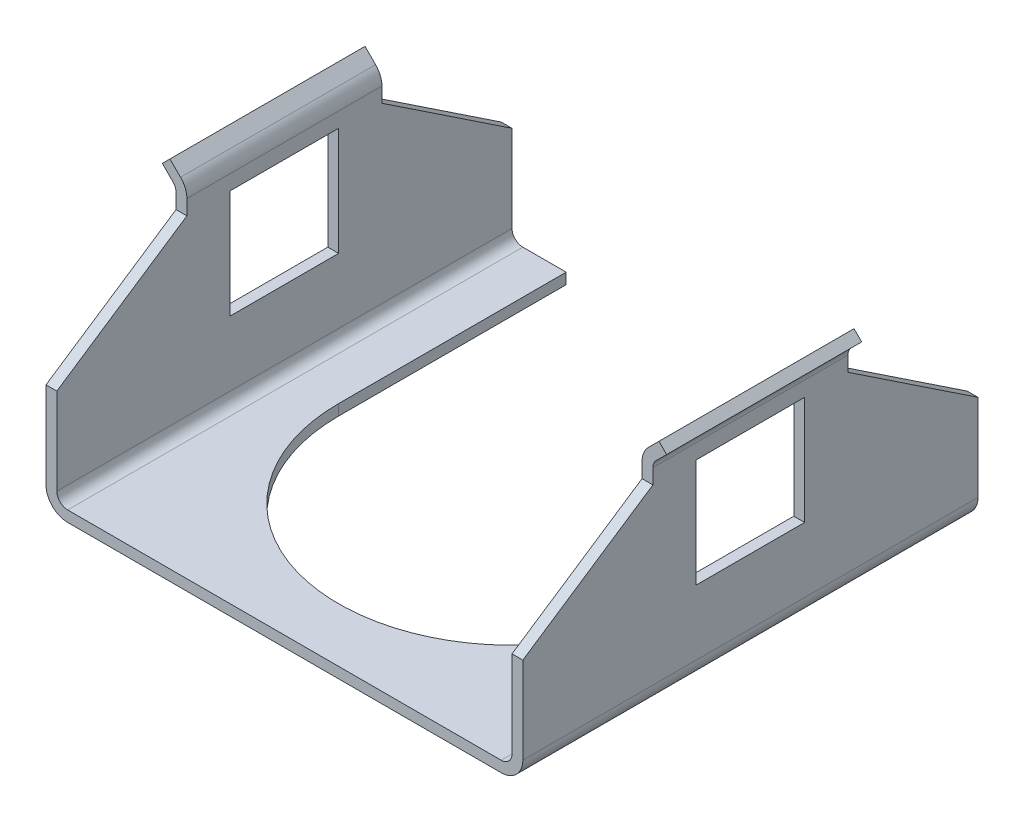
SolidWorks part; units mm, degrees
ref_plane "Front Plane" through (0, 0, 0) normal (0, 0, 1) x (1, 0, 0)
ref_plane "Top Plane" through (0, 0, 0) normal (0, 1, 0) x (1, 0, 0)
ref_plane "Right Plane" through (0, 0, 0) normal (1, 0, 0) x (0, 0, -1)
sketch "Sketch2" plane through (0, 0, 0) normal (0, 1, 0) x (1, 0, 0)
  line L1 (-10.5, 10.5) -> (10.5, 10.5)
  line L2 (-10.5, 10.5) -> (-10.5, -10.5)
  line L3 (-10.5, -10.5) -> (10.5, -10.5)
  line L4 (10.5, 10.5) -> (10.5, -10.5)
  line L5 (-10.5, 10.5) -> (10.5, -10.5) construction
  line L6 (-10.5, -10.5) -> (10.5, 10.5) construction
  circle A0 centre (0, 0) radius 8
  dimension "D1" = 16
  dimension "D2" = 21
extrude "Boss-Extrude1" add sketch "Sketch2" along normal blind 0.5
sketch "Sketch3" plane through (0, 0.5, 0) normal (0, 1, 0) x (1, 0, 0)
  line L0 (-8, 0) -> (-8, 10.5)
  line L1 (10.5, 10.5) -> (-10.5, 10.5) construction
  line L2 (-8, 10.5) -> (-8, 11.596)
  line L3 (8, 0) -> (8, 11.596)
  line L4 (-8, 11.596) -> (8, 11.596)
  circle A0 centre (0, 0) radius 8 construction
  arc A1 (-8, 0) -> (8, 0) centre (0, 0) ccw
extrude "Cut-Extrude1" cut sketch "Sketch3" against normal blind 1.5
sketch "Sketch4" plane through (10.5, 0, 0) normal (1, 0, 0) x (0, 0, -1)
  line L0 (-10.5, 0.5) -> (-10.5, 0) construction
  line L1 (-10.5, 0) -> (10.5, 0)
  line L2 (-10.5, 0) -> (-10.5, 9)
  line L3 (-10.5, 9) -> (10.5, 9)
  line L4 (10.5, 0) -> (10.5, 9)
  dimension "D1" = 9
  dimension "D2" = 21
extrude "Boss-Extrude2" add sketch "Sketch4" along normal blind 0.5
sketch "Sketch5" plane through (11, 0, 0) normal (1, 0, 0) x (0, 0, -1)
  line L0 (0, 0) -> (0, 9) construction
  line L1 (0, 9) -> (2.5, 9) construction
  line L3 (2.5, 9) -> (-2.5, 9)
  line L4 (2.5, 9) -> (2.5, 4)
  line L5 (2.5, 4) -> (-2.5, 4)
  line L6 (-2.5, 9) -> (-2.5, 4)
  dimension "D1" = 9
  dimension "D2" = 2.5
  dimension "D3" = 5
extrude "Cut-Extrude2" cut sketch "Sketch5" against normal through all both and the other way through all
sketch "Sketch6" plane through (11, 0, 0) normal (1, 0, 0) x (0, 0, -1)
  line L0 (10.5, 5) -> (4.5, 9)
  line L1 (10.5, 0) -> (10.5, 9) construction
  line L2 (10.5, 9) -> (2.5, 9) construction
  line L3 (4.5, 9) -> (4.5, 12.4835)
  line L4 (4.5, 12.4835) -> (11.7348, 12.4835)
  line L5 (11.7348, 12.4835) -> (11.7348, 5)
  line L6 (11.7348, 5) -> (10.5, 5)
  line L7 (-10.5, 0) -> (10.5, 0) construction
  dimension "D1" = 5
  dimension "D2" = 6
extrude "Cut-Extrude3" cut sketch "Sketch6" against normal blind 1.5
mirror "Mirror1" about plane through (0, 0, 0) normal (0, 0, 1) of "Cut-Extrude3"
fillet "Fillet1" radius 1 1 edges at (11, 0, 0)
fillet "Fillet2" radius 0.5 1 edges at (10.5, 0.5, 0)
sketch "Sketch7" plane through (0, 0, 0) normal (0, 0, 1) x (1, 0, 0)
  line L0 (10.75, 9) -> (10.75, 10)
  line L1 (10.5, 9) -> (11, 9) construction
  line L2 (10.75, 10) -> (11.4571, 10.7071)
  dimension "D1" = 1
  dimension "D2" = 1
  dimension "D3" = 135
extrude "Extrude-Thin1" add sketch "Sketch7" along normal mid plane 9 thin thin type mid plane wall 0.5
fillet "Fillet3" radius 0.5 1 edges at (11, 9.8964, 0)
fillet "Fillet4" radius 1 1 edges at (10.5, 10.1036, 0)
mirror "Mirror2" about plane through (0, 0, 0) normal (1, 0, 0) of "Extrude-Thin1", "Boss-Extrude2"
sketch "Sketch8" plane through (-10.5, 0, 0) normal (1, 0, 0) x (0, 0, -1)
  line L0 (4.5, 9) -> (4.5, 13.5104)
  line L1 (-2.5, 9) -> (2.5, 9)
  line L2 (-2.5, 9) -> (-2.5, 4)
  line L3 (-2.5, 4) -> (2.5, 4)
  line L4 (2.5, 9) -> (2.5, 4)
  line L5 (4.5, 13.5104) -> (11.9049, 13.5104)
  line L6 (11.9049, 13.5104) -> (11.9049, 4.9857)
  line L7 (11.9049, 4.9857) -> (10.5, 5)
  line L8 (10.5, 5) -> (4.5, 9)
  line L9 (0, 9.6839) -> (0, -1.1793) construction
  line L10 (-10.5, 5) -> (-4.5, 9)
  line L11 (-11.9049, 4.9857) -> (-10.5, 5)
  line L12 (-11.9049, 13.5104) -> (-11.9049, 4.9857)
  line L13 (-4.5, 13.5104) -> (-11.9049, 13.5104)
  line L14 (-4.5, 9) -> (-4.5, 13.5104)
  point P21 (0, 0)
extrude "Cut-Extrude4" cut sketch "Sketch8" against normal through all both and the other way through all
fillet "Fillet5" radius 0.5 2 edges at (-11, 9.8964, 0) (-10.5, 0.5, 0)
fillet "Fillet6" radius 1 2 edges at (-11, 0, 0) (-10.5, 10.1036, 0)
